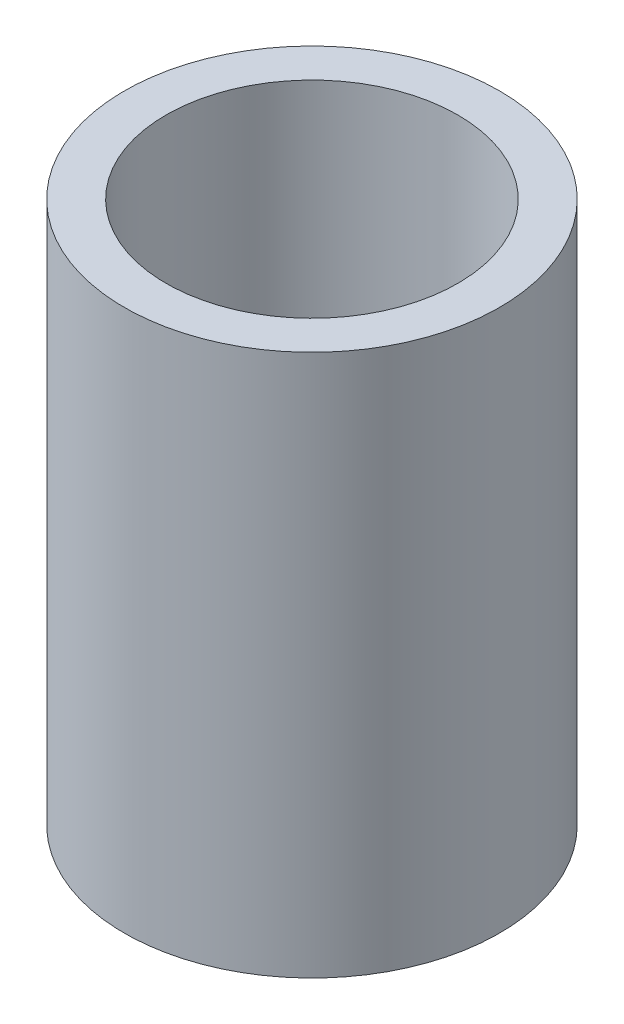
SolidWorks part; units mm, degrees
ref_plane "Front" through (0, 0, 0) normal (0, 0, 1) x (1, 0, 0)
ref_plane "Top" through (0, 0, 0) normal (0, 1, 0) x (1, 0, 0)
ref_plane "Right" through (0, 0, 0) normal (1, 0, 0) x (0, 0, -1)
sketch "Sketch1" plane through (0, 0, 0) normal (0, 1, 0) x (1, 0, 0)
  circle A0 centre (0, 0) radius 4.5
  circle A1 centre (0, 0) radius 3.5
extrude "Boss-Extrude1" add sketch "Sketch1" along normal blind 13
